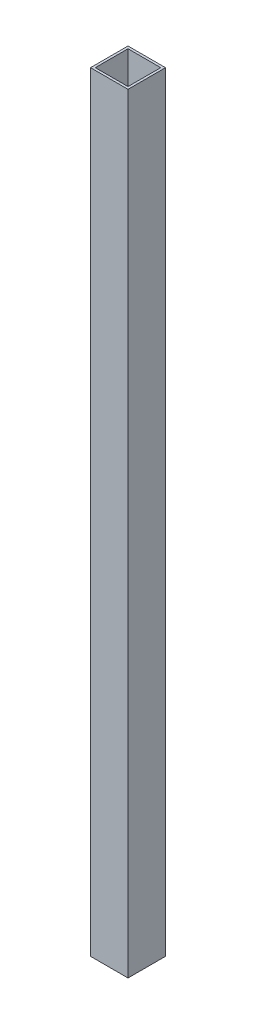
SolidWorks part; units mm, degrees
ref_plane "Front Plane" through (0, 0, 0) normal (0, 0, 1) x (1, 0, 0)
ref_plane "Top Plane" through (0, 0, 0) normal (0, 1, 0) x (1, 0, 0)
ref_plane "Right Plane" through (0, 0, 0) normal (1, 0, 0) x (0, 0, -1)
sketch "Sketch1" plane through (0, 0, 0) normal (0, 1, 0) x (1, 0, 0)
  line L1 (-9.5, -9.5) -> (9.5, -9.5)
  line L2 (-9.5, -9.5) -> (-9.5, 9.5)
  line L3 (-9.5, 9.5) -> (9.5, 9.5)
  line L4 (9.5, -9.5) -> (9.5, 9.5)
  line L5 (-9.5, -9.5) -> (9.5, 9.5) construction
  line L6 (-9.5, 9.5) -> (9.5, -9.5) construction
  line L7 (-8.3, -8.3) -> (8.3, -8.3)
  line L8 (-8.3, -8.3) -> (-8.3, 8.3)
  line L9 (-8.3, 8.3) -> (8.3, 8.3)
  line L10 (8.3, -8.3) -> (8.3, 8.3)
  line L11 (-8.3, -8.3) -> (8.3, 8.3) construction
  line L12 (-8.3, 8.3) -> (8.3, -8.3) construction
  point P0 (0, 0)
  point P6 (0, 0)
  dimension "D1" = 1.2
  dimension "D2" = 1.2
  dimension "D3" = 19
extrude "Boss-Extrude1" add sketch "Sketch1" along normal mid plane 390
